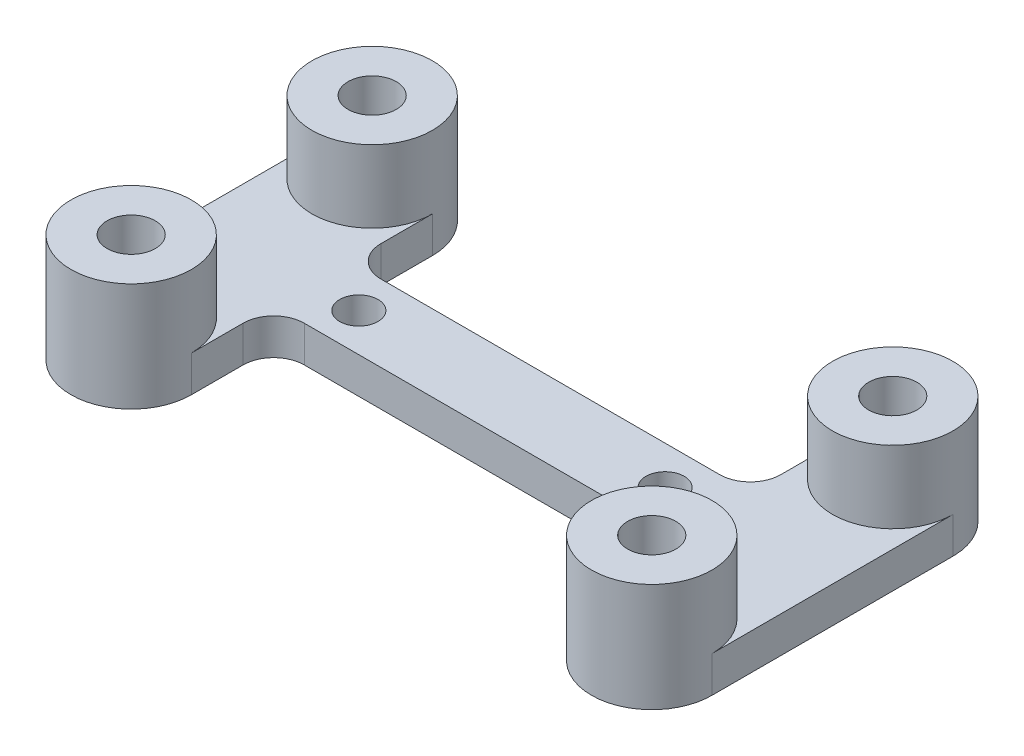
SolidWorks part; units mm, degrees
ref_plane "Front Plane" through (0, 0, 0) normal (0, 0, 1) x (1, 0, 0)
ref_plane "Top Plane" through (0, 0, 0) normal (0, 1, 0) x (1, 0, 0)
ref_plane "Right Plane" through (0, 0, 0) normal (1, 0, 0) x (0, 0, -1)
sketch "Sketch4" plane through (0, 0, 0) normal (0, 1, 0) x (1, 0, 0)
  line L1 (-21.59, -9.9949) -> (21.59, -9.9949) construction
  line L2 (-21.59, -9.9949) -> (-21.59, 9.9949) construction
  line L3 (-21.59, 9.9949) -> (21.59, 9.9949) construction
  line L4 (21.59, -9.9949) -> (21.59, 9.9949) construction
  line L5 (-21.59, -9.9949) -> (21.59, 9.9949) construction
  line L6 (-21.59, 9.9949) -> (21.59, -9.9949) construction
  circle A0 centre (-21.59, 9.9949) radius 5
  circle A1 centre (-21.59, -9.9949) radius 5
  circle A2 centre (21.59, 9.9949) radius 5
  circle A3 centre (21.59, -9.9949) radius 5
  circle A4 centre (21.59, -9.9949) radius 2
  circle A5 centre (21.59, 9.9949) radius 2
  circle A6 centre (-21.59, -9.9949) radius 2
  circle A7 centre (-21.59, 9.9949) radius 2
  point P0 (0, 0)
  dimension "D3" = 4
  dimension "D4" = 10
  dimension "D5" = 4
  dimension "D6" = 10
  dimension "D7" = 4
  dimension "D8" = 10
  dimension "D9" = 10
  dimension "D10" = 4
  dimension "D1" = 19.9898
  dimension "D2" = 43.18
extrude "Boss-Extrude3" add sketch "Sketch4" along normal blind 9
sketch "Sketch5" plane through (0, 0, 0) normal (0, 1, 0) x (1, 0, 0)
  line L1 (-26.59, -9.9949) -> (-16.59, -9.9949)
  line L2 (-26.59, -9.9949) -> (-26.59, 9.9949)
  line L3 (-26.59, 9.9949) -> (-16.59, 9.9949)
  line L4 (-16.59, -9.9949) -> (-16.59, 9.9949)
  line L5 (-26.59, -9.9949) -> (-16.59, 9.9949) construction
  line L6 (-26.59, 9.9949) -> (-16.59, -9.9949) construction
  line L7 (0, -3.175) -> (-16.59, -3.175)
  line L8 (0, -3.175) -> (0, 3.175)
  line L9 (0, 3.175) -> (-16.59, 3.175)
  line L10 (-16.59, -3.175) -> (-16.59, 3.175)
  line L11 (0, -3.175) -> (-16.59, 3.175) construction
  line L12 (0, 3.175) -> (-16.59, -3.175) construction
  circle A0 centre (-21.59, 9.9949) radius 5 construction
  circle A1 centre (-21.59, 9.9949) radius 2
  circle A2 centre (-21.59, -9.9949) radius 2
  point P0 (-21.59, 0)
  point P9 (-8.295, 0)
  dimension "D1" = 6.35
extrude "Boss-Extrude4" add sketch "Sketch5" along normal blind 3 contours L1 L4 L3 L2 | L8 L9 L4 L7
mirror "Mirror1" about plane through (0, 0, 0) normal (1, 0, 0) of "Boss-Extrude4"
sketch "Sketch6" plane through (0, 3, 0) normal (0, 1, 0) x (1, 0, 0)
  line L0 (-12.7, 0) -> (12.7, 0) construction
  circle A0 centre (-12.7, 0) radius 1.5875
  circle A1 centre (12.7, 0) radius 1.5875
  dimension "D2" = 3.175
  dimension "D3" = 3.175
  dimension "D1" = 25.4
extrude "Cut-Extrude1" cut sketch "Sketch6" against normal through all
fillet "Fillet1" radius 2.54 4 edges at (16.59, 1.5, 3.175) (16.59, 1.5, -3.175) (-16.59, 1.5, -3.175) (-16.59, 1.5, 3.175)
